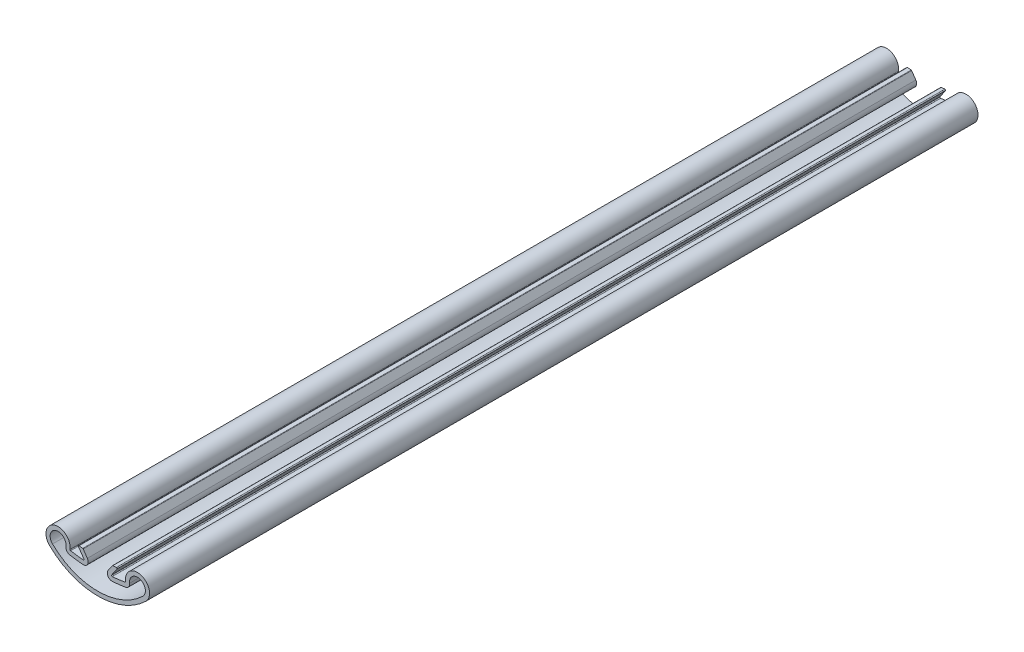
SolidWorks part; units mm, degrees
ref_plane "Front Plane" through (0, 0, 0) normal (0, 0, 1) x (1, 0, 0)
ref_plane "Top Plane" through (0, 0, 0) normal (0, 1, 0) x (1, 0, 0)
ref_plane "Right Plane" through (0, 0, 0) normal (1, 0, 0) x (0, 0, -1)
sketch "Sketch1" plane through (0, 0, 0) normal (0, 0, 1) x (1, 0, 0)
  line L0 (-8, -46.8215) -> (-8, -44.2832) construction
  line L1 (0, 0) -> (0, -52.5463) construction
  line L2 (8, -44.2832) -> (8, -46.8215) construction
  line L3 (-4.7439, -46.9314) -> (-6, -45.1027) construction
  line L4 (-4.0054, -48.0064) -> (-5.596, -45.6908)
  line L5 (6, -45.1027) -> (4.7439, -46.9314) construction
  line L6 (5.596, -45.6908) -> (4.0054, -48.0064)
  line L7 (-3.0163, -47.327) -> (-4.2183, -45.577)
  line L8 (4.2183, -45.577) -> (3.0163, -47.327)
  line L10 (-4.0054, -48.0064) -> (-6, -45.1027) construction
  line L11 (-3.0163, -47.327) -> (-5.0109, -44.4232) construction
  line L12 (5.0109, -44.4232) -> (3.0163, -47.327) construction
  line L13 (6, -45.1027) -> (4.0054, -48.0064) construction
  arc A0 (-8.0378, -47.6301) -> (-13.9394, -49.6267) centre (-11.5, -47.1169) ccw
  arc A2 (10, -43.8748) -> (-10, -43.8748) centre (0, 0) ccw construction
  arc A3 (-13.9394, -49.6267) -> (13.9394, -49.6267) centre (0, -35.2847) ccw
  arc A5 (4.1875, -48.3189) -> (7.8725, -47.8568) centre (0, 0) ccw
  arc A6 (13.9394, -49.6267) -> (8.0378, -47.6301) centre (11.5, -47.1169) ccw
  arc A8 (-7.8725, -47.8568) -> (-4.1875, -48.3189) centre (0, 0) ccw
  arc A9 (7.8725, -47.8568) -> (8.0378, -47.6301) centre (7.84, -47.6595) ccw
  arc A10 (4.0054, -48.0064) -> (4.1875, -48.3189) centre (4.1703, -48.1196) ccw
  arc A11 (-8.0378, -47.6301) -> (-7.8725, -47.8568) centre (-7.84, -47.6595) ccw
  arc A12 (-4.0054, -48.0064) -> (-4.1875, -48.3189) centre (-4.1703, -48.1196) cw
  arc A13 (-3.0163, -47.327) -> (-4.2911, -49.5144) centre (-4.1703, -48.1196) cw
  arc A14 (-8.0672, -49.0409) -> (-4.2911, -49.5144) centre (0, 0) ccw
  arc A15 (-9.2249, -47.4542) -> (-8.0672, -49.0409) centre (-7.84, -47.6595) ccw
  arc A16 (-9.2249, -47.4542) -> (-13.103, -48.7662) centre (-11.5, -47.1169) ccw
  arc A17 (-13.103, -48.7662) -> (13.103, -48.7662) centre (0, -35.2847) ccw
  arc A18 (13.103, -48.7662) -> (9.2249, -47.4542) centre (11.5, -47.1169) ccw
  arc A19 (8.0672, -49.0409) -> (9.2249, -47.4542) centre (7.84, -47.6595) ccw
  arc A20 (4.2911, -49.5144) -> (8.0672, -49.0409) centre (0, 0) ccw
  arc A21 (3.0163, -47.327) -> (4.2911, -49.5144) centre (4.1703, -48.1196) ccw
  arc A23 (4.3641, -45.4911) -> (5.4075, -45.3789) centre (0, 0) ccw
  arc A24 (-6.0264, -45.3009) -> (6.0264, -45.3009) centre (0, 0) ccw
  arc A25 (-5.4075, -45.3789) -> (-4.3641, -45.4911) centre (0, 0) ccw
  arc A26 (5.4075, -45.3789) -> (5.596, -45.6908) centre (5.4312, -45.5775) cw
  arc A27 (4.3641, -45.4911) -> (4.2183, -45.577) centre (4.3832, -45.6902) ccw
  arc A28 (-4.2183, -45.577) -> (-4.3641, -45.4911) centre (-4.3832, -45.6902) ccw
  arc A29 (-5.4075, -45.3789) -> (-5.596, -45.6908) centre (-5.4312, -45.5775) ccw
  point P29 (-8.0721, -47.8235)
  dimension "D1" = 7
  dimension "D2" = 7
  dimension "D3" = 40
  dimension "D4" = 0.2
  dimension "D7" = 0.2
  dimension "D5" = 1.2
  dimension "D6" = 0.2
extrude "Boss-Extrude1" add sketch "Sketch1" against normal up to surface (240 mm away)
ref_plane "平面1" through (0, 0, -135) normal (0, 0, 1) x (1, 0, 0)
sketch "ｽｹｯﾁ2" plane through (0, 0, -135) normal (0, 0, 1) x (1, 0, 0)
  line L1 (18.9707, -60.7147) -> (-18.9707, -60.7147)
  line L2 (18.9707, -60.7147) -> (18.9707, -40.1789)
  line L3 (18.9707, -40.1789) -> (-18.9707, -40.1789)
  line L4 (-18.9707, -60.7147) -> (-18.9707, -40.1789)
  line L5 (18.9707, -60.7147) -> (-18.9707, -40.1789) construction
  line L6 (18.9707, -40.1789) -> (-18.9707, -60.7147) construction
  point P0 (0, -50.4468)
extrude "ｶｯﾄ - 押し出し1" [suppressed] cut sketch "ｽｹｯﾁ2" against normal through all
